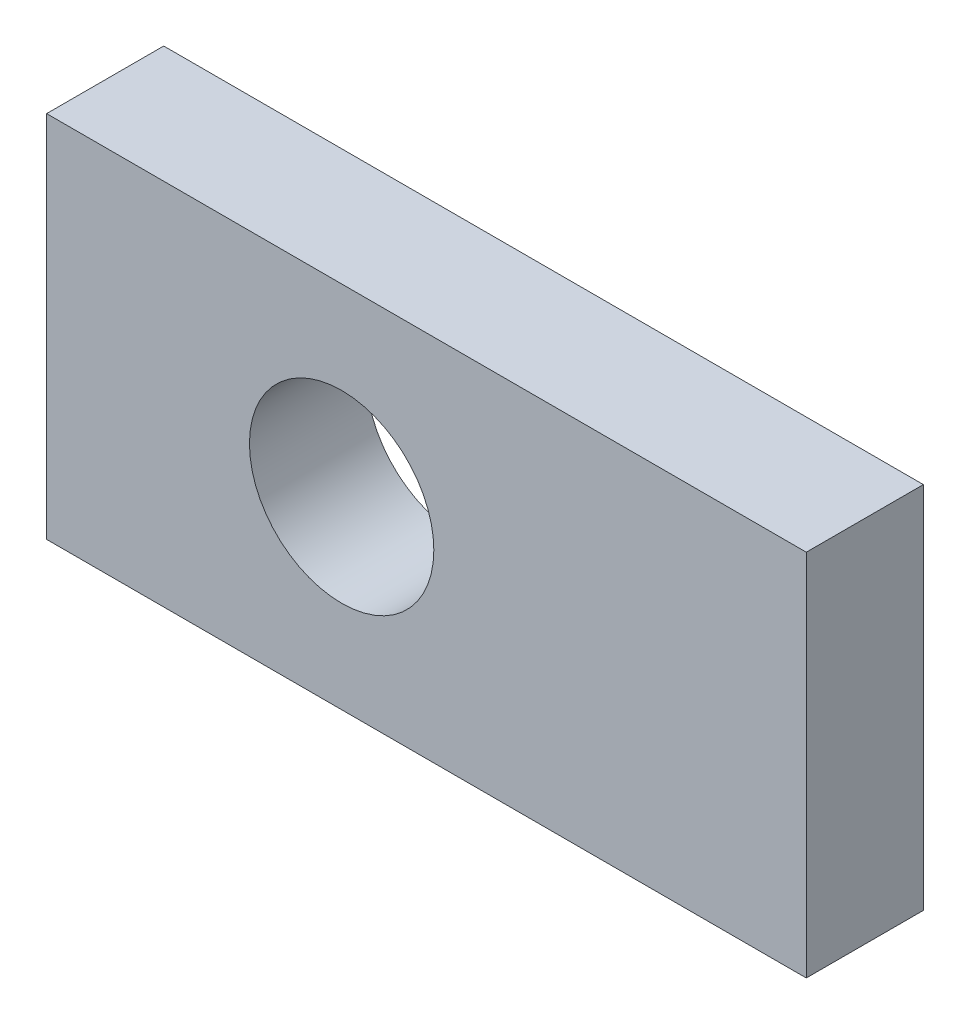
SolidWorks part; units mm, degrees
material "Cobre"
ref_plane "Alzado" through (0, 0, 0) normal (0, 0, 1) x (1, 0, 0)
ref_plane "Planta" through (0, 0, 0) normal (0, 1, 0) x (1, 0, 0)
ref_plane "Vista lateral" through (0, 0, 0) normal (1, 0, 0) x (0, 0, -1)
sketch "Croquis1" plane through (0, 0, 0) normal (0, 1, 0) x (1, 0, 0)
  line L1 (10.3, -1.5875) -> (-10.3, -1.5875)
  line L2 (10.3, -1.5875) -> (10.3, 1.5875)
  line L3 (10.3, 1.5875) -> (-10.3, 1.5875)
  line L4 (-10.3, -1.5875) -> (-10.3, 1.5875)
  line L5 (10.3, -1.5875) -> (-10.3, 1.5875) construction
  line L6 (10.3, 1.5875) -> (-10.3, -1.5875) construction
  point P0 (0, 0)
  dimension "D1" = 20.6
  dimension "D2" = 3.175
extrude "Saliente-Extruir1" add sketch "Croquis1" along normal blind 10
sketch "Croquis2" plane through (0, 0, 1.5875) normal (0, 0, 1) x (1, 0, 0)
  line L0 (10.3, 5) -> (-2.3, 5) construction
  line L1 (10.3, 10) -> (10.3, 0) construction
  circle A0 centre (-2.3, 5) radius 2.5
  dimension "D1" = 5
  dimension "D2" = 12.6
extrude "Cortar-Extruir1" cut sketch "Croquis2" against normal through all
